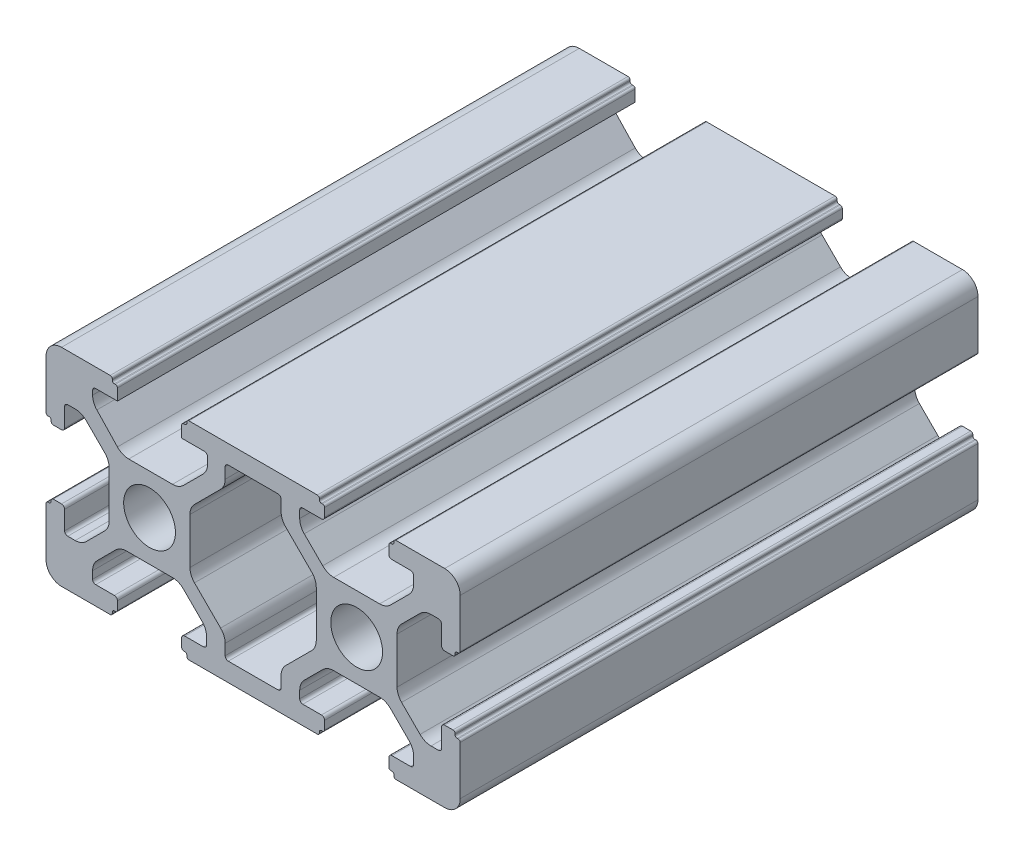
SolidWorks part; units mm, degrees
material "6063-O"
ref_plane "Front Plane" through (0, 0, 0) normal (0, 0, 1) x (1, 0, 0)
ref_plane "Top Plane" through (0, 0, 0) normal (0, 1, 0) x (1, 0, 0)
ref_plane "Right Plane" through (0, 0, 0) normal (1, 0, 0) x (0, 0, -1)
sketch "Sketch1" plane through (0, 0, 0) normal (0, 0, 1) x (1, 0, 0)
  line L0 (1.5, 0) -> (6.2, 0)
  line L1 (40, 1.5) -> (40, 6.2)
  line L2 (38.5, 20) -> (33.8, 20)
  line L3 (0, 18.5) -> (0, 13.8)
  line L4 (17.6, 1.8) -> (22.4, 1.8)
  line L5 (32.218, 13.9) -> (27.782, 13.9)
  line L6 (26.1, 12.218) -> (26.1, 7.782)
  line L7 (17.6, 18.2) -> (22.4, 18.2)
  line L8 (12.218, 13.9) -> (7.9864, 13.9)
  line L9 (6.1, 12.218) -> (6.1, 7.782)
  line L10 (7.782, 6.1) -> (12.218, 6.1)
  line L11 (13.9, 7.782) -> (13.9, 12.218)
  line L12 (27.782, 6.1) -> (32.218, 6.1)
  line L13 (33.9, 7.782) -> (33.9, 12.218)
  line L14 (26.7213, 14.3393) -> (24.9393, 16.1213)
  line L15 (33.2787, 14.3393) -> (35.0607, 16.1213)
  line L16 (34.3393, 13.2787) -> (36.1213, 15.0607)
  line L17 (25.6607, 6.7213) -> (23.1393, 4.2)
  line L18 (15.2, 1.8) -> (13.4, 1.8)
  line L19 (26.7213, 5.6607) -> (24.9393, 3.8787)
  line L20 (24.8, 1.8) -> (26.6, 1.8)
  line L21 (15.3, 18.2) -> (13.1, 18.2)
  line L22 (13.2787, 14.3393) -> (15.1607, 16.2213)
  line L23 (14.3393, 13.2787) -> (16.8607, 15.8)
  line L24 (5.6607, 6.7213) -> (3.8787, 4.9393)
  line L25 (6.7213, 5.6607) -> (4.9393, 3.8787)
  line L26 (6.897, 14.3689) -> (4.9106, 16.4674)
  line L27 (5.6607, 13.2787) -> (3.8787, 15.0607)
  line L28 (14.3393, 6.7213) -> (16.8607, 4.2)
  line L29 (13.2787, 5.6607) -> (15.0607, 3.8787)
  line L30 (24.8, 18.2) -> (26.6, 18.2)
  line L31 (25.6607, 13.2787) -> (23.1393, 15.8)
  line L32 (34.3393, 6.7213) -> (36.1213, 4.9393)
  line L33 (33.2787, 5.6607) -> (35.0607, 3.8787)
  line L34 (1.8, 15.2) -> (1.8, 13.4)
  line L35 (24.5, 2.1) -> (24.5, 2.818)
  line L36 (4.5, 2.1) -> (4.5, 2.818)
  line L37 (2.818, 4.5) -> (2.1, 4.5)
  line L38 (4.5, 17.9) -> (4.5, 17.4986)
  line L39 (2.818, 15.5) -> (2.1, 15.5)
  line L40 (15.6, 17.9) -> (15.6, 17.282)
  line L41 (15.5, 2.818) -> (15.5, 2.1)
  line L42 (38.2, 15.2) -> (38.2, 13.4)
  line L43 (35.5, 2.818) -> (35.5, 2.1)
  line L44 (37.182, 4.5) -> (37.9, 4.5)
  line L45 (35.5, 17.182) -> (35.5, 17.9)
  line L46 (37.182, 15.5) -> (37.9, 15.5)
  line L47 (17.3, 2.1) -> (17.3, 3.1393)
  line L48 (22.7, 2.1) -> (22.7, 3.1393)
  line L49 (17.3, 17.9) -> (17.3, 16.8607)
  line L50 (22.7, 17.9) -> (22.7, 16.8607)
  line L51 (24.5, 17.9) -> (24.5, 17.182)
  line L52 (6.9, 19.3) -> (6.9, 18.2)
  line L53 (13.1, 19.3) -> (13.1, 18.2)
  line L54 (6.9, 1.5) -> (6.9, 0.7)
  line L55 (13.1, 1.5) -> (13.1, 0.7)
  line L56 (13.8, 0) -> (26.2, 0)
  line L57 (6.6, 1.8) -> (4.8, 1.8)
  line L58 (6.9, 18.2) -> (4.8, 18.2)
  line L59 (6.2, 20) -> (1.5, 20)
  line L60 (39.3, 6.9) -> (38.5, 6.9)
  line L61 (39.3, 13.1) -> (38.5, 13.1)
  line L62 (1.5, 13.1) -> (0.7, 13.1)
  line L63 (1.5, 6.9) -> (0.7, 6.9)
  line L64 (0, 6.2) -> (0, 1.5)
  line L65 (1.8, 6.6) -> (1.8, 4.8)
  line L66 (38.2, 6.6) -> (38.2, 4.8)
  line L67 (40, 13.8) -> (40, 18.5)
  line L68 (33.1, 19.3) -> (33.1, 18.5)
  line L69 (26.9, 19.3) -> (26.9, 18.5)
  line L70 (26.9, 1.5) -> (26.9, 0.7)
  line L71 (33.1, 1.5) -> (33.1, 0.7)
  line L72 (33.8, 0) -> (38.5, 0)
  line L73 (33.4, 1.8) -> (35.2, 1.8)
  line L74 (26.2, 20) -> (13.8, 20)
  line L75 (33.4, 18.2) -> (35.2, 18.2)
  line L76 (6.7, 0.5) -> (6.6, 0.5)
  line L77 (6.4, 0.3) -> (6.4, 0.2)
  line L78 (13.3, 0.5) -> (13.4, 0.5)
  line L79 (13.6, 0.3) -> (13.6, 0.2)
  line L80 (26.7, 0.5) -> (26.6, 0.5)
  line L81 (26.4, 0.3) -> (26.4, 0.2)
  line L82 (33.3, 0.5) -> (33.4, 0.5)
  line L83 (33.6, 0.3) -> (33.6, 0.2)
  line L85 (6.4, 19.8) -> (6.4, 19.7)
  line L86 (6.6, 19.5) -> (6.7, 19.5)
  line L87 (13.6, 19.8) -> (13.6, 19.7)
  line L88 (13.4, 19.5) -> (13.3, 19.5)
  line L89 (26.4, 19.8) -> (26.4, 19.7)
  line L90 (26.6, 19.5) -> (26.7, 19.5)
  line L91 (33.6, 19.8) -> (33.6, 19.7)
  line L92 (33.4, 19.5) -> (33.3, 19.5)
  line L93 (0.5, 13.3) -> (0.5, 13.4)
  line L94 (0.3, 13.6) -> (0.2, 13.6)
  line L95 (0.5, 6.7) -> (0.5, 6.6)
  line L96 (0.3, 6.4) -> (0.2, 6.4)
  line L97 (39.5, 13.3) -> (39.5, 13.4)
  line L98 (39.7, 13.6) -> (39.8, 13.6)
  line L99 (39.5, 6.7) -> (39.5, 6.6)
  line L100 (39.7, 6.4) -> (39.8, 6.4)
  circle A0 centre (10, 10) radius 2.5
  circle A1 centre (30, 10) radius 2.5
  arc A2 (38.5, 0) -> (40, 1.5) centre (38.5, 1.5) ccw
  arc A3 (40, 18.5) -> (38.5, 20) centre (38.5, 18.5) ccw
  arc A4 (1.5, 0) -> (0, 1.5) centre (1.5, 1.5) cw
  arc A5 (1.5, 20) -> (0, 18.5) centre (1.5, 18.5) ccw
  arc A6 (26.7213, 5.6607) -> (27.782, 6.1) centre (27.782, 4.6) cw
  arc A7 (32.218, 6.1) -> (33.2787, 5.6607) centre (32.218, 4.6) cw
  arc A8 (33.9, 7.782) -> (34.3393, 6.7213) centre (35.4, 7.782) ccw
  arc A9 (33.2787, 14.3393) -> (32.218, 13.9) centre (32.218, 15.4) cw
  arc A10 (14.3393, 6.7213) -> (13.9, 7.782) centre (15.4, 7.782) cw
  arc A11 (14.3393, 13.2787) -> (13.9, 12.218) centre (15.4, 12.218) ccw
  arc A12 (25.6607, 6.7213) -> (26.1, 7.782) centre (24.6, 7.782) ccw
  arc A13 (26.1, 12.218) -> (25.6607, 13.2787) centre (24.6, 12.218) ccw
  arc A14 (27.782, 13.9) -> (26.7213, 14.3393) centre (27.782, 15.4) cw
  arc A15 (5.6607, 13.2787) -> (6.1, 12.218) centre (4.6, 12.218) cw
  arc A16 (5.6607, 6.7213) -> (6.1, 7.782) centre (4.6, 7.782) ccw
  arc A17 (13.2787, 5.6607) -> (12.218, 6.1) centre (12.218, 4.6) ccw
  arc A18 (6.7213, 5.6607) -> (7.782, 6.1) centre (7.782, 4.6) cw
  arc A19 (13.2787, 14.3393) -> (12.218, 13.9) centre (12.218, 15.4) cw
  arc A20 (6.897, 14.3689) -> (7.9864, 13.9) centre (7.9864, 15.4) ccw
  arc A21 (36.1213, 4.9393) -> (37.182, 4.5) centre (37.182, 6) ccw
  arc A22 (36.1213, 15.0607) -> (37.182, 15.5) centre (37.182, 14) cw
  arc A23 (35.0607, 16.1213) -> (35.5, 17.182) centre (34, 17.182) ccw
  arc A24 (24.5, 17.182) -> (24.9393, 16.1213) centre (26, 17.182) ccw
  arc A25 (22.7, 16.8607) -> (23.1393, 15.8) centre (24.2, 16.8607) ccw
  arc A26 (17.3, 16.8607) -> (16.8607, 15.8) centre (15.8, 16.8607) cw
  arc A27 (4.9106, 16.4674) -> (4.5, 17.4986) centre (6, 17.4986) cw
  arc A28 (15.6, 17.282) -> (15.1607, 16.2213) centre (14.1, 17.282) cw
  arc A29 (3.8787, 15.0607) -> (2.818, 15.5) centre (2.818, 14) ccw
  arc A30 (3.8787, 4.9393) -> (2.818, 4.5) centre (2.818, 6) cw
  arc A31 (4.9393, 3.8787) -> (4.5, 2.818) centre (6, 2.818) ccw
  arc A32 (35.0607, 3.8787) -> (35.5, 2.818) centre (34, 2.818) cw
  arc A33 (24.9393, 3.8787) -> (24.5, 2.818) centre (26, 2.818) ccw
  arc A34 (22.7, 3.1393) -> (23.1393, 4.2) centre (24.2, 3.1393) cw
  arc A35 (17.3, 3.1393) -> (16.8607, 4.2) centre (15.8, 3.1393) ccw
  arc A36 (15.5, 2.818) -> (15.0607, 3.8787) centre (14, 2.818) ccw
  arc A37 (1.8, 6.6) -> (1.5, 6.9) centre (1.5, 6.6) ccw
  arc A38 (1.8, 13.4) -> (1.5, 13.1) centre (1.5, 13.4) cw
  arc A39 (17.6, 18.2) -> (17.3, 17.9) centre (17.6, 17.9) ccw
  arc A40 (22.4, 1.8) -> (22.7, 2.1) centre (22.4, 2.1) ccw
  arc A41 (17.6, 1.8) -> (17.3, 2.1) centre (17.6, 2.1) cw
  arc A42 (15.2, 1.8) -> (15.5, 2.1) centre (15.2, 2.1) ccw
  arc A43 (6.6, 1.8) -> (6.9, 1.5) centre (6.6, 1.5) cw
  arc A44 (13.4, 1.8) -> (13.1, 1.5) centre (13.4, 1.5) ccw
  arc A45 (24.8, 1.8) -> (24.5, 2.1) centre (24.8, 2.1) cw
  arc A46 (35.2, 1.8) -> (35.5, 2.1) centre (35.2, 2.1) ccw
  arc A47 (26.6, 1.8) -> (26.9, 1.5) centre (26.6, 1.5) cw
  arc A48 (33.4, 1.8) -> (33.1, 1.5) centre (33.4, 1.5) ccw
  arc A49 (26.9, 18.5) -> (26.6, 18.2) centre (26.6, 18.5) cw
  arc A50 (33.1, 18.5) -> (33.4, 18.2) centre (33.4, 18.5) ccw
  arc A51 (37.9, 4.5) -> (38.2, 4.8) centre (37.9, 4.8) ccw
  arc A52 (38.5, 13.1) -> (38.2, 13.4) centre (38.5, 13.4) cw
  arc A53 (38.5, 6.9) -> (38.2, 6.6) centre (38.5, 6.6) ccw
  arc A54 (38.2, 15.2) -> (37.9, 15.5) centre (37.9, 15.2) ccw
  arc A55 (35.2, 18.2) -> (35.5, 17.9) centre (35.2, 17.9) cw
  arc A56 (24.8, 18.2) -> (24.5, 17.9) centre (24.8, 17.9) ccw
  arc A57 (22.4, 18.2) -> (22.7, 17.9) centre (22.4, 17.9) cw
  arc A58 (15.3, 18.2) -> (15.6, 17.9) centre (15.3, 17.9) cw
  arc A59 (4.5, 17.9) -> (4.8, 18.2) centre (4.8, 17.9) cw
  arc A60 (1.8, 15.2) -> (2.1, 15.5) centre (2.1, 15.2) cw
  arc A61 (1.8, 4.8) -> (2.1, 4.5) centre (2.1, 4.8) ccw
  arc A62 (4.5, 2.1) -> (4.8, 1.8) centre (4.8, 2.1) ccw
  arc A63 (34.3393, 13.2787) -> (33.9, 12.218) centre (35.4, 12.218) ccw
  arc A64 (6.4, 0.2) -> (6.2, 0) centre (6.2, 0.2) cw
  arc A65 (6.6, 0.5) -> (6.4, 0.3) centre (6.6, 0.3) ccw
  arc A66 (6.7, 0.5) -> (6.9, 0.7) centre (6.7, 0.7) ccw
  arc A67 (13.6, 0.2) -> (13.8, 0) centre (13.8, 0.2) ccw
  arc A68 (13.4, 0.5) -> (13.6, 0.3) centre (13.4, 0.3) cw
  arc A69 (13.3, 0.5) -> (13.1, 0.7) centre (13.3, 0.7) cw
  arc A70 (26.4, 0.2) -> (26.2, 0) centre (26.2, 0.2) cw
  arc A71 (26.6, 0.5) -> (26.4, 0.3) centre (26.6, 0.3) ccw
  arc A72 (26.7, 0.5) -> (26.9, 0.7) centre (26.7, 0.7) ccw
  arc A73 (33.6, 0.2) -> (33.8, 0) centre (33.8, 0.2) ccw
  arc A74 (33.4, 0.5) -> (33.6, 0.3) centre (33.4, 0.3) cw
  arc A75 (33.3, 0.5) -> (33.1, 0.7) centre (33.3, 0.7) cw
  arc A76 (39.8, 6.4) -> (40, 6.2) centre (39.8, 6.2) cw
  arc A77 (39.5, 6.6) -> (39.7, 6.4) centre (39.7, 6.6) ccw
  arc A78 (39.5, 6.7) -> (39.3, 6.9) centre (39.3, 6.7) ccw
  arc A79 (39.5, 13.3) -> (39.3, 13.1) centre (39.3, 13.3) cw
  arc A80 (39.5, 13.4) -> (39.7, 13.6) centre (39.7, 13.4) cw
  arc A81 (39.8, 13.6) -> (40, 13.8) centre (39.8, 13.8) ccw
  arc A82 (33.3, 19.5) -> (33.1, 19.3) centre (33.3, 19.3) ccw
  arc A83 (33.6, 19.7) -> (33.4, 19.5) centre (33.4, 19.7) cw
  arc A84 (33.6, 19.8) -> (33.8, 20) centre (33.8, 19.8) cw
  arc A85 (26.7, 19.5) -> (26.9, 19.3) centre (26.7, 19.3) cw
  arc A86 (26.4, 19.7) -> (26.6, 19.5) centre (26.6, 19.7) ccw
  arc A87 (26.4, 19.8) -> (26.2, 20) centre (26.2, 19.8) ccw
  arc A88 (0.2, 6.4) -> (0, 6.2) centre (0.2, 6.2) ccw
  arc A89 (0.5, 6.6) -> (0.3, 6.4) centre (0.3, 6.6) cw
  arc A90 (0.5, 6.7) -> (0.7, 6.9) centre (0.7, 6.7) cw
  arc A91 (13.3, 19.5) -> (13.1, 19.3) centre (13.3, 19.3) ccw
  arc A92 (13.6, 19.7) -> (13.4, 19.5) centre (13.4, 19.7) cw
  arc A93 (13.6, 19.8) -> (13.8, 20) centre (13.8, 19.8) cw
  arc A94 (6.2, 20) -> (6.4, 19.8) centre (6.2, 19.8) cw
  arc A95 (6.7, 19.5) -> (6.9, 19.3) centre (6.7, 19.3) cw
  arc A96 (6.4, 19.7) -> (6.6, 19.5) centre (6.6, 19.7) ccw
  arc A97 (0.5, 13.3) -> (0.7, 13.1) centre (0.7, 13.3) ccw
  arc A98 (0.2, 13.6) -> (0, 13.8) centre (0.2, 13.8) cw
  arc A99 (0.5, 13.4) -> (0.3, 13.6) centre (0.3, 13.4) ccw
  point P87 (0, 0)
  point P178 (1.8, 6.9)
  point P181 (1.8, 13.1)
  point P186 (22.7, 1.8)
  point P193 (6.9, 1.8)
  point P204 (33.1, 1.8)
  point P209 (33.1, 18.2)
  point P216 (38.2, 6.9)
  point P243 (6.9, 0.5)
  point P248 (13.6, 0.5)
  point P257 (26.9, 0.5)
extrude "Boss-Extrude2" add sketch "Sketch1" along normal blind 50 contours A57 L7 A39 L49 A26 L23 A11 L11 A10 L28 A35 L47 A41 L4 A40 L48 A34 L17 A12 L6 A13 L31 A25 L50 | A0 | A1 | L59 A5 L3 A98 L94 A99 L93 A97 L62 A38 L34 A60 L39 A29 L27 A15 L9 A16 L24 A30 L37 A61 L65 A37 L63 A90 L95 A89 L96 A88 L64 A4 L0 A64 L77 A65 L76 A66 L54 A43 L57 A62 L36 A31 L25 A18 L10 A17 L29 A36 L41 A42 L18 A44 L55 A69 L78 A68 L79 A67 L56 A70 L81 A71 L80 A72 L70 A47 L20 A45 L35 A33 L19 A6 L12 A7 L33 A32 L43 A46 L73 A48 L71 A75 L82 A74 L83 A73 L72 A2 L1 A76 L100 A77 L99 A78 L60 A53 L66 A51 L44 A21 L32 A8 L13 A63 L16 A22 L46 A54 L42 A52 L61 A79 L97 A80 L98 A81 L67 A3 L2 A84 L91 A83 L92 A82 L68 A50 L75 A55 L45 A23 L15 A9 L5 A14 L14 A24 L51 A56 L30 A49 L69 A85 L90 A86 L89 A87 L74 A93 L87 A92 L88 A91 L53 L21 A58 L40 A28 L22 A19 L8 A20 L26 A27 L38 A59 L58 L52 A95 L86 A96 L85 A94
